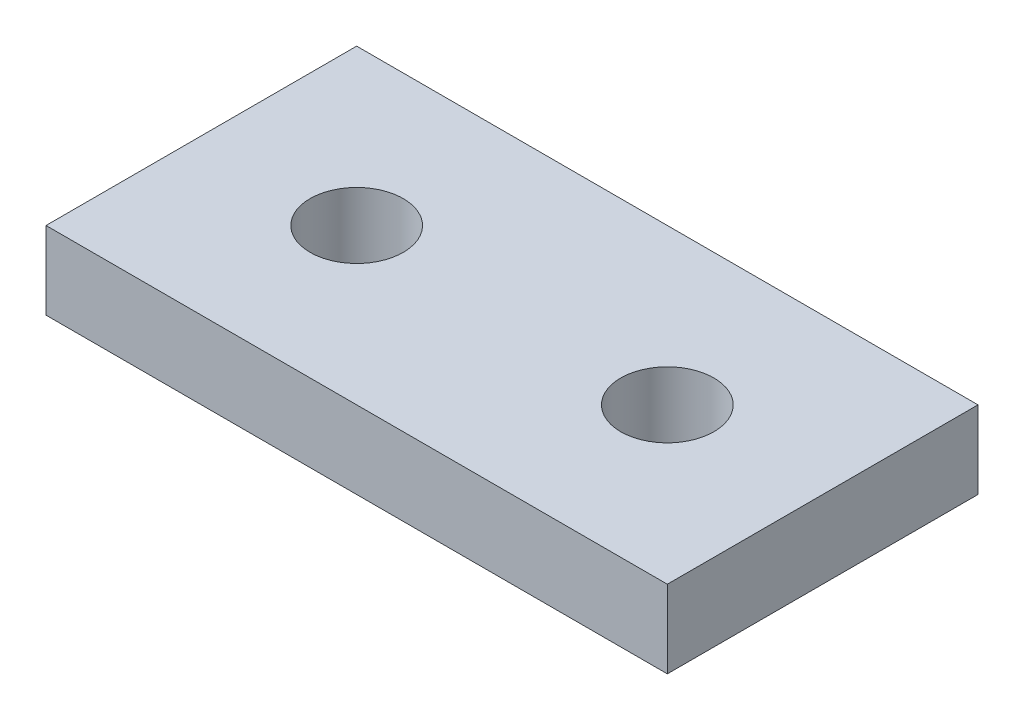
SolidWorks part; units mm, degrees
ref_plane "Front Plane" through (0, 0, 0) normal (0, 0, 1) x (1, 0, 0)
ref_plane "Top Plane" through (0, 0, 0) normal (0, 1, 0) x (1, 0, 0)
ref_plane "Right Plane" through (0, 0, 0) normal (1, 0, 0) x (0, 0, -1)
sketch "Sketch1" plane through (0, 0, 0) normal (0, 1, 0) x (1, 0, 0)
  line L0 (-11.25, -12.6563) -> (-11.25, 7.3437) construction
  line L1 (-31.25, 7.3437) -> (8.75, 7.3437)
  line L2 (-31.25, 7.3437) -> (-31.25, -12.6563)
  line L3 (-31.25, -12.6563) -> (8.75, -12.6563)
  line L4 (8.75, 7.3437) -> (8.75, -12.6563)
  line L5 (-11.25, 7.3437) -> (-31.25, -12.6563) construction
  line L6 (-11.25, -12.6563) -> (8.75, 7.3437) construction
  circle A0 centre (-21.25, -2.6563) radius 3
  circle A1 centre (-1.25, -2.6563) radius 3
  point P10 (0, 0)
  dimension "D3" = 6
  dimension "D4" = 6
  dimension "D1" = 40
  dimension "D2" = 20
extrude "Boss-Extrude1" add sketch "Sketch1" along normal blind 5
